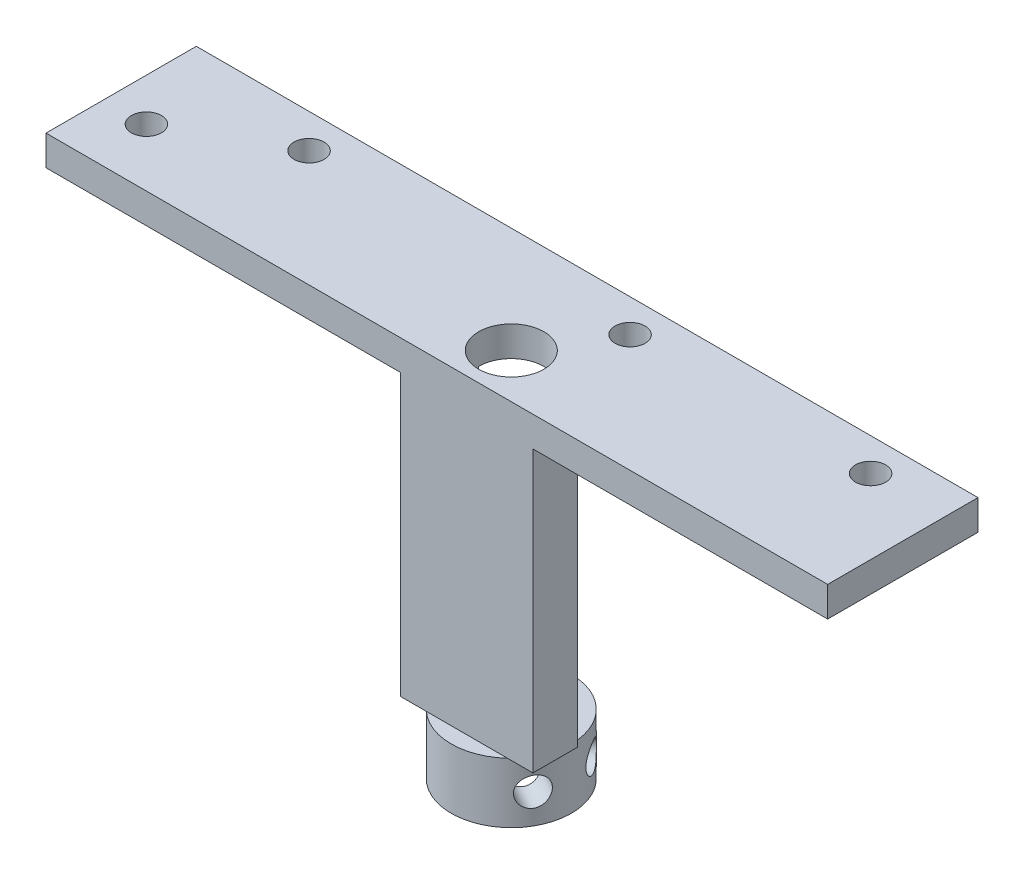
SolidWorks part; units mm, degrees
ref_plane "前视基准面" through (0, 0, 0) normal (0, 0, 1) x (1, 0, 0)
ref_plane "上视基准面" through (0, 0, 0) normal (0, 1, 0) x (1, 0, 0)
ref_plane "右视基准面" through (0, 0, 0) normal (1, 0, 0) x (0, 0, -1)
other "Configuration Table"
sketch "草图1" plane through (0, 0, 0) normal (0, 1, 0) x (1, 0, 0)
  line L1 (-39, -7.5) -> (39, -7.5)
  line L2 (-39, -7.5) -> (-39, 7.5)
  line L3 (-39, 7.5) -> (39, 7.5)
  line L4 (39, -7.5) -> (39, 7.5)
  line L5 (-39, -7.5) -> (39, 7.5) construction
  line L6 (-39, 7.5) -> (39, -7.5) construction
  point P0 (0, 0)
  dimension "D1" = 15
  dimension "D2" = 78
extrude "凸台-拉伸1" add sketch "草图1" along normal blind 3 contours L2 L1 L4 L3
sketch "草图3" plane through (0, 3, 0) normal (0, 1, 0) x (1, 0, 0)
  line L0 (-39, -7.5) -> (-39, 7.5) construction
  line L1 (-39, 7.5) -> (39, 7.5) construction
  circle A0 centre (-34.76, -1.72) radius 1.5
  circle A1 centre (-24.35, 4.1) radius 1.5
  circle A2 centre (31.56, 4.2217) radius 1.5
  circle A3 centre (7.56, 4.2217) radius 1.5
  dimension "D1" = 4.24
  dimension "D2" = 10.41
  dimension "D3" = 3.4
  dimension "D4" = 5.82
  dimension "D5" = 31.91
  dimension "D6" = 24
extrude "切除-拉伸1" cut sketch "草图3" against normal blind 3
sketch "草图4" plane through (0, 3, 0) normal (0, 1, 0) x (1, 0, 0)
  line L0 (-39, -7.5) -> (-39, 7.5) construction
  circle A0 centre (-3, -1.2342) radius 6
  dimension "D1" = 36
extrude "凸台-拉伸2" add sketch "草图4" along normal blind 18
sketch "草图5" plane through (0, 21, 0) normal (0, 1, 0) x (1, 0, 0)
  circle A0 centre (-3, -1.2342) radius 4.5
extrude "切除-拉伸2" cut sketch "草图5" against normal blind 21
hole_wizard "Ø2.0mm 暗销孔2" positions "3D草图5" profile "草图8" hole size "Ø2.0" standard "ANSI Metric"
sketch3d "3D草图5"
  point P0 (-7.9013, 17.3421, 4.6949)
  point P2 (1.0718, 17.1648, 5.6411)
sketch "草图8" plane through (-7.9013, 17.3421, 4.6949) normal (0, 1, 0) x (0.5768, 0, 0.8169)
  line L0 (0, 0) -> (0, 6)
  line L1 (0, 6) -> (1.5, 4.5)
  line L2 (1.5, 4.5) -> (1.5, 0)
  line L5 (1.5, 0) -> (0, 0)
  line L10 (0, 6) -> (-1.5, 4.5) construction
  line L11 (0, -6.35) -> (0, 107.95) construction
  dimension "孔直径" = 3
  dimension "孔深度" = 6
  dimension "导头角度" = 90
sketch "草图10" plane through (0, 0, -7.5) normal (0, 0, -1) x (-1, 0, 0)
  line L0 (39, 3) -> (-39, 3) construction
  line L1 (0, 3) -> (6, 3)
  line L2 (0, 3) -> (0, 13)
  line L3 (0, 13) -> (6, 13)
  line L4 (6, 3) -> (6, 13)
  dimension "D1" = 6
  dimension "D2" = 10
extrude "切除-拉伸3" cut sketch "草图10" against normal blind 7
sketch "草图13" plane through (0, 0, -7.5) normal (0, 0, -1) x (-1, 0, 0)
  line L0 (39, 3) -> (-39, 3) construction
  line L1 (-6.6034, 3) -> (13.2323, 3)
  line L2 (-6.6034, 3) -> (-6.6034, 24.6102)
  line L3 (-6.6034, 24.6102) -> (13.2323, 24.6102)
  line L4 (13.2323, 3) -> (13.2323, 24.6102)
extrude "切除-拉伸4" cut sketch "草图13" against normal blind 20
sketch "草图14" plane through (0, 3, 0) normal (0, 1, 0) x (1, 0, 0)
  line L1 (-8.751, 3.9817) -> (2.7721, 3.9817)
  line L2 (-8.751, 3.9817) -> (-8.751, -6.5086)
  line L3 (-8.751, -6.5086) -> (2.7721, -6.5086)
  line L4 (2.7721, 3.9817) -> (2.7721, -6.5086)
extrude "凸台-拉伸3" add sketch "草图14" against normal blind 3
sketch "草图18" plane through (0, 0, 0) normal (0, -1, 0) x (1, 0, 0)
  line L1 (-39, 7.5) -> (39, 7.5)
  line L2 (-39, 7.5) -> (-39, 15.5)
  line L3 (-39, 15.5) -> (39, 15.5)
  line L4 (39, 7.5) -> (39, 15.5)
  dimension "D1" = 8
extrude "凸台-拉伸4" add sketch "草图18" against normal blind 3
sketch "草图19" plane through (0, 0, 0) normal (0, -1, 0) x (1, 0, 0)
  line L0 (39, 15.5) -> (-39, 15.5) construction
  line L1 (-17.5447, 15.5) -> (19.2232, 15.5)
  line L2 (-17.5447, 15.5) -> (-17.5447, 13)
  line L3 (-17.5447, 13) -> (19.2232, 13)
  line L4 (19.2232, 15.5) -> (19.2232, 13)
  dimension "D1" = 2.5
extrude "凸台-拉伸5" add sketch "草图19" along normal blind 12.5
sketch "草图20" plane through (0, 0, 13) normal (0, 0, -1) x (-1, 0, 0)
  circle A0 centre (-6.7687, -6.2144) radius 1.65
  circle A1 centre (6.2313, -6.2144) radius 1.65
  dimension "D1" = 13
sketch "草图23" plane through (0, 0, 13) normal (0, 0, -1) x (-1, 0, 0)
  line L0 (-19.2232, -12.5) -> (-19.2232, 0) construction
  circle A4 centre (-8.6032, -6.0559) radius 1.65
  circle A5 centre (2.5968, -6.0559) radius 1.65
  dimension "D1" = 10.62
  dimension "D2" = 11.2
extrude "切除-拉伸6" cut sketch "草图23" against normal blind 12.5
sketch "草图24" plane through (0, 0, 13) normal (0, 0, -1) x (-1, 0, 0)
  circle A0 centre (-8.6032, -6.0559) radius 1.65 construction
  circle A1 centre (-8.6032, -6.0559) radius 1.65
  circle A2 centre (2.5968, -6.0559) radius 1.65 construction
  circle A3 centre (2.5968, -6.0559) radius 1.65
  circle A4 centre (4.1968, -6.0559) radius 1.6
  dimension "D2" = 12.8
  dimension "D1" = 11.2
sketch "草图25" plane through (0, 0, 13) normal (0, 0, -1) x (-1, 0, 0)
  line L1 (0.2124, -3.7444) -> (4.449, -3.7444)
  line L2 (0.2124, -3.7444) -> (0.2124, -9.1085)
  line L3 (0.2124, -9.1085) -> (4.449, -9.1085)
  line L4 (4.449, -3.7444) -> (4.449, -9.1085)
extrude "凸台-拉伸7" add sketch "草图25" against normal blind 2.5
sketch "草图26" plane through (0, 0, 13) normal (0, 0, -1) x (-1, 0, 0)
  circle A0 centre (4.1968, -6.0559) radius 1.6 construction
  circle A1 centre (4.1968, -6.0559) radius 1.6
extrude "切除-拉伸7" cut sketch "草图26" against normal blind 2.5
sketch "草图27" plane through (0, 0, 13) normal (0, 0, -1) x (-1, 0, 0)
  line L1 (-13.0523, -3.3946) -> (8.2937, -3.3946)
  line L2 (-13.0523, -3.3946) -> (-13.0523, -9.9889)
  line L3 (-13.0523, -9.9889) -> (8.2937, -9.9889)
  line L4 (8.2937, -3.3946) -> (8.2937, -9.9889)
extrude "凸台-拉伸8" add sketch "草图27" against normal blind 2.5
sketch "草图28" plane through (0, 0, 13) normal (0, 0, -1) x (-1, 0, 0)
  line L1 (-19.2232, -12.5) -> (17.544, -12.5)
  line L2 (-19.2232, -12.5) -> (-19.2232, -18.4182)
  line L3 (-19.2232, -18.4182) -> (17.544, -18.4182)
  line L4 (17.544, -12.5) -> (17.544, -18.4182)
extrude "凸台-拉伸9" add sketch "草图28" against normal blind 2.5
sketch "草图29" plane through (0, 0, 13) normal (0, 0, -1) x (-1, 0, 0)
  line L1 (-14.4639, -11.6442) -> (13.1964, -11.6442)
  line L2 (-14.4639, -11.6442) -> (-14.4639, -15.1442)
  line L3 (-14.4639, -15.1442) -> (13.1964, -15.1442)
  line L4 (13.1964, -11.6442) -> (13.1964, -15.1442)
  dimension "D1" = 3.5
extrude "切除-拉伸9" cut sketch "草图29" against normal blind 2.5
sketch "草图30" plane through (0, 3, 0) normal (0, 1, 0) x (1, 0, 0)
  line L0 (39, -15.5) -> (39, 7.5) construction
  line L1 (-39, -15.5) -> (39, -15.5)
  line L2 (-39, -15.5) -> (-39, -7.5)
  line L3 (-39, -7.5) -> (39, -7.5)
  line L4 (39, -15.5) -> (39, -7.5)
  line L5 (-39, 7.5) -> (39, 7.5) construction
  dimension "D1" = 15
extrude "切除-拉伸10" cut sketch "草图30" against normal blind 100
sketch "草图31" plane through (0, 0, 0) normal (0, -1, 0) x (1, 0, 0)
  line L0 (39, 7.5) -> (-39, 7.5) construction
  line L1 (-29.754, 7.5) -> (31.0662, 7.5)
  line L2 (-29.754, 7.5) -> (-29.754, 4.5)
  line L3 (-29.754, 4.5) -> (31.0662, 4.5)
  line L4 (31.0662, 7.5) -> (31.0662, 4.5)
  dimension "D1" = 3
extrude "凸台-拉伸10" add sketch "草图31" along normal blind 49
sketch "草图32" plane through (0, 0, 4.5) normal (0, 0, -1) x (-1, 0, 0)
  line L0 (-24.1534, -35.8541) -> (23.8466, -35.8541)
  line L1 (-24.1893, -43.0541) -> (23.8107, -43.0541)
  line L2 (-24.1893, -43.0541) -> (-24.1893, -46.2541)
  line L3 (-24.1893, -46.2541) -> (23.8107, -46.2541)
  line L4 (23.8107, -43.0541) -> (23.8107, -46.2541)
  line L5 (-24.1534, -35.8541) -> (-24.1534, -39.0541)
  line L6 (-24.1534, -39.0541) -> (23.8466, -39.0541)
  line L7 (23.8466, -35.8541) -> (23.8466, -39.0541)
  line L8 (-24.1733, -28.6541) -> (23.8267, -28.6541)
  line L9 (-24.1733, -28.6541) -> (-24.1733, -31.8541)
  line L10 (-24.1733, -31.8541) -> (23.8267, -31.8541)
  line L11 (23.8267, -28.6541) -> (23.8267, -31.8541)
  line L12 (-24.2052, -21.4541) -> (23.7948, -21.4541)
  line L13 (-24.2052, -21.4541) -> (-24.2052, -24.6541)
  line L14 (-24.2052, -24.6541) -> (23.7948, -24.6541)
  line L15 (23.7948, -21.4541) -> (23.7948, -24.6541)
  line L16 (-24.1756, -14.2541) -> (23.8244, -14.2541)
  line L17 (-24.1756, -14.2541) -> (-24.1756, -17.4541)
  line L18 (-24.1756, -17.4541) -> (23.8244, -17.4541)
  line L19 (23.8244, -14.2541) -> (23.8244, -17.4541)
  line L20 (-24.2763, -8.0541) -> (23.7237, -8.0541)
  line L21 (-24.2763, -8.0541) -> (-24.2763, -11.2541)
  line L22 (-24.2763, -11.2541) -> (23.7237, -11.2541)
  line L23 (23.7237, -8.0541) -> (23.7237, -11.2541)
  dimension "D1" = 3.2
  dimension "D2" = 48
  dimension "D3" = 4
  dimension "D4" = 4
  dimension "D5" = 4
  dimension "D6" = 4
  dimension "D7" = 3
extrude "切除-拉伸11" cut sketch "草图32" against normal blind 49 contours L19 L16 L17 L18 | L15 L12 L13 L14 | L11 L8 L9 L10 | L7 L0 L5 L6 | L4 L1 L2 L3 | L20 L23 L22 L21
sketch "草图33" plane through (31.0662, 0, 0) normal (1, 0, 0) x (0, 0, -1)
  line L3 (-7.5, 0) -> (7.5, 0)
  line L4 (-7.5, 0) -> (-7.5, -49.0597)
  line L5 (-7.5, -49.0597) -> (7.5, -49.0597)
  line L6 (7.5, 0) -> (7.5, -49.0597)
extrude "切除-拉伸12" cut sketch "草图33" against normal blind 100
sketch "草图34" plane through (0, 0, 0) normal (0, -1, 0) x (1, 0, 0)
  line L0 (39, 7.5) -> (39, -7.5) construction
  circle A0 centre (3, 3.0716) radius 4.25
  dimension "D1" = 36
extrude "凸台-拉伸11" add sketch "草图34" along normal blind 49
sketch "草图35" plane through (0, -49, 0) normal (0, -1, 0) x (1, 0, 0)
  circle A0 centre (3, 3.0716) radius 6
extrude "凸台-拉伸12" add sketch "草图35" against normal blind 6
sketch "草图36" plane through (0, 0, -7.5) normal (0, 0, -1) x (-1, 0, 0)
  line L0 (1.25, -43) -> (1.25, 0) construction
  line L1 (-7.25, 0) -> (1.25, 0)
  line L2 (-7.25, 0) -> (-7.25, -40)
  line L3 (-7.25, -40) -> (1.25, -40)
  line L4 (1.25, 0) -> (1.25, -40)
  dimension "D1" = 40
extrude "切除-拉伸13" cut sketch "草图36" against normal blind 11
sketch "草图37" plane through (0, -49, 0) normal (0, -1, 0) x (1, 0, 0)
  circle A0 centre (3, 3.0716) radius 3.25
extrude "切除-拉伸16" cut sketch "草图37" against normal blind 100
sketch "草图39" plane through (0, 0, 3.5) normal (0, 0, -1) x (-1, 0, 0)
  line L0 (1.2283, -40) -> (1.2283, 0) construction
  line L1 (-7.2283, -40) -> (1.2283, -40)
  line L2 (-7.2283, -40) -> (-7.2283, -24)
  line L3 (-7.2283, -24) -> (1.2283, -24)
  line L4 (1.2283, -40) -> (1.2283, -24)
  dimension "D1" = 16
extrude "切除-拉伸17" cut sketch "草图39" against normal blind 1.25
hole_wizard "Ø3.0mm 暗销孔1" positions "3D草图7" profile "草图41" hole size "Ø3.0" standard "ANSI Metric"
sketch3d "3D草图7"
  point P0 (3.0692, -45.9266, -2.928)
sketch "草图41" plane through (3.0692, -45.9266, -2.928) normal (0, 1, 0) x (-0.9999, 0, -0.0115)
  line L0 (0, 0) -> (0, 5)
  line L1 (0, 5) -> (1.425, 4.1438)
  line L2 (1.425, 4.1438) -> (1.425, 0)
  line L5 (1.425, 0) -> (0, 0)
  line L10 (0, 5) -> (-1.425, 4.1438) construction
  line L11 (0, -6.35) -> (0, 107.95) construction
  dimension "孔直径" = 2.85
  dimension "孔深度" = 5
  dimension "导头角度" = 118
ref_plane "基准面1" through (0, -46, 0) normal (0, -1, 0) x (-1, 0, 0)
sketch "草图42" plane through (0, -46, 0) normal (0, -1, 0) x (-1, 0, 0)
  line L0 (-3, -3.0716) -> (-3, 2.9284)
  line L1 (-3, -3.0716) -> (2.1962, -6.0716)
  line L2 (-3, -3.0716) -> (-8.1962, -6.0716)
  circle A0 centre (-3, -3.0716) radius 6 construction
  dimension "D1" = 120
  dimension "D2" = 120
hole_wizard "Ø3.0mm 暗销孔2" positions "3D草图8" profile "草图44" hole size "Ø3.0" standard "ANSI Metric"
sketch3d "3D草图8"
  point P0 (-2.1944, -45.9809, 6.0747)
sketch "草图44" plane through (-2.1944, -45.9809, 6.0747) normal (0, 1, 0) x (0.5005, 0, 0.8657)
  line L0 (0, 0) -> (0, 5)
  line L1 (0, 5) -> (1.425, 4.1438)
  line L2 (1.425, 4.1438) -> (1.425, 0)
  line L5 (1.425, 0) -> (0, 0)
  line L10 (0, 5) -> (-1.425, 4.1438) construction
  line L11 (0, -6.35) -> (0, 107.95) construction
  dimension "孔直径" = 2.85
  dimension "孔深度" = 5
  dimension "导头角度" = 118
hole_wizard "Ø3.0mm 暗销孔3" positions "3D草图9" profile "草图45" hole size "Ø3.0" standard "ANSI Metric"
sketch3d "3D草图9"
  point P0 (8.2058, -46.04, 6.0548)
sketch "草图45" plane through (8.2058, -46.04, 6.0548) normal (0, 1, 0) x (0.4972, 0, -0.8676)
  line L0 (0, 0) -> (0, 5)
  line L1 (0, 5) -> (1.425, 4.1438)
  line L2 (1.425, 4.1438) -> (1.425, 0)
  line L5 (1.425, 0) -> (0, 0)
  line L10 (0, 5) -> (-1.425, 4.1438) construction
  line L11 (0, -6.35) -> (0, 107.95) construction
  dimension "孔直径" = 2.85
  dimension "孔深度" = 5
  dimension "导头角度" = 118
sketch "草图46" plane through (0, 3, 0) normal (0, 1, 0) x (1, 0, 0)
  line L0 (39, -7.5) -> (-39, -7.5) construction
  line L1 (-3.6375, -7.5) -> (9.5896, -7.5)
  line L2 (-3.6375, -7.5) -> (-3.6375, -3.0716)
  line L3 (-3.6375, -3.0716) -> (9.5896, -3.0716)
  line L4 (9.5896, -7.5) -> (9.5896, -3.0716)
extrude "凸台-拉伸13" add sketch "草图46" against normal blind 46
sketch "草图48" plane through (0, -49, 0) normal (0, -1, 0) x (1, 0, 0)
  line L1 (-0.25, 3.0716) -> (6.25, 3.0716)
  line L2 (-0.25, 3.0716) -> (6.25, 3.0716)
  arc A1 (6.25, 3.0716) -> (-0.25, 3.0716) centre (3, 3.0716) ccw
  arc A2 (6.25, 3.0716) -> (-0.25, 3.0716) centre (3, 3.0716) ccw
  dimension "D1" = 0
extrude "切除-拉伸18" cut sketch "草图48" against normal blind 55
sketch "草图49" plane through (0, 0, 0) normal (0, -1, 0) x (1, 0, 0)
  line L9 (-0.25, 3.0716) -> (-3.6375, 3.0716)
  line L10 (-3.6375, 3.0716) -> (-3.6375, 7.5)
  line L11 (-3.6375, 7.5) -> (-39, 7.5)
  line L12 (-39, 7.5) -> (-39, -7.5)
  line L13 (-39, -7.5) -> (39, -7.5)
  line L14 (39, -7.5) -> (39, 7.5)
  line L15 (39, 7.5) -> (9.5896, 7.5)
  line L16 (9.5896, 7.5) -> (9.5896, 3.0716)
  line L17 (9.5896, 3.0716) -> (6.25, 3.0716)
  line L18 (-0.25, 3.0716) -> (-3.6375, 3.0716)
  line L19 (-3.6375, 3.0716) -> (-3.6375, 7.5)
  line L20 (-3.6375, 7.5) -> (-39, 7.5)
  line L21 (-39, 7.5) -> (-39, -7.5)
  line L22 (-39, -7.5) -> (39, -7.5)
  line L23 (39, -7.5) -> (39, 7.5)
  line L24 (39, 7.5) -> (9.5896, 7.5)
  line L25 (9.5896, 7.5) -> (9.5896, 3.0716)
  line L26 (9.5896, 3.0716) -> (6.25, 3.0716)
  arc A1 (-0.25, 3.0716) -> (6.25, 3.0716) centre (3, 3.0716) ccw
  arc A2 (-0.25, 3.0716) -> (6.25, 3.0716) centre (3, 3.0716) ccw
  dimension "D1" = 0
extrude "凸台-拉伸14" add sketch "草图49" along normal blind 15
sketch "草图50" plane through (0, 0, 0) normal (0, 1, 0) x (1, 0, 0)
  circle A1 centre (-34.76, -1.72) radius 1.5
  circle A2 centre (-34.76, -1.72) radius 1.5
  dimension "D1" = 0
extrude "切除-拉伸19" cut sketch "草图50" against normal blind 15
sketch "草图51" plane through (0, 0, 0) normal (0, 1, 0) x (1, 0, 0)
  circle A1 centre (-24.35, 4.1) radius 1.5
  circle A2 centre (-24.35, 4.1) radius 1.5
  dimension "D1" = 0
extrude "切除-拉伸20" cut sketch "草图51" against normal blind 15
sketch "草图52" plane through (0, 0, 0) normal (0, 1, 0) x (1, 0, 0)
  circle A1 centre (7.56, 4.2217) radius 1.5
  circle A2 centre (7.56, 4.2217) radius 1.5
  dimension "D1" = 0
extrude "切除-拉伸21" cut sketch "草图52" against normal blind 15
sketch "草图53" plane through (0, 0, 0) normal (0, 1, 0) x (1, 0, 0)
  circle A1 centre (31.56, 4.2217) radius 1.5
  circle A2 centre (31.56, 4.2217) radius 1.5
  dimension "D1" = 0
extrude "切除-拉伸22" cut sketch "草图53" against normal blind 15
sketch "草图54" plane through (0, 3, 0) normal (0, 1, 0) x (1, 0, 0)
  line L4 (-39, 7.5) -> (-39, -7.5)
  line L5 (-39, -7.5) -> (39, -7.5)
  line L6 (39, -7.5) -> (39, 7.5)
  line L7 (39, 7.5) -> (-39, 7.5)
  line L8 (-39, 7.5) -> (-39, -7.5)
  line L9 (-39, -7.5) -> (39, -7.5)
  line L10 (39, -7.5) -> (39, 7.5)
  line L11 (39, 7.5) -> (-39, 7.5)
  dimension "D1" = 0
extrude "切除-拉伸23" cut sketch "草图54" against normal blind 15
ref_plane "基准面2" through (0, -46, 0) normal (0, -1, 0) x (-1, 0, 0)
sketch "草图55" plane through (0, -46, 0) normal (0, -1, 0) x (-1, 0, 0)
  line L0 (-3, -3.0716) -> (2.1962, -0.0716)
  line L1 (-3, -3.0716) -> (-8.1962, -0.0716)
  line L2 (-3, -3.0716) -> (-3, 2.9284) construction
  circle A0 centre (-3, -3.0716) radius 6 construction
  dimension "D1" = 60
  dimension "D2" = 60
hole_wizard "Ø3.0mm 暗销孔4" positions "3D草图10" profile "草图56" hole size "Ø3.0" standard "ANSI Metric"
sketch3d "3D草图10"
  point P0 (-2.2068, -45.9744, 0.0901)
sketch "草图56" plane through (-2.2068, -45.9744, 0.0901) normal (0, 1, 0) x (-0.4969, 0, 0.8678)
  line L0 (0, 0) -> (0, 5)
  line L1 (0, 5) -> (1.425, 4.1438)
  line L2 (1.425, 4.1438) -> (1.425, 0)
  line L5 (1.425, 0) -> (0, 0)
  line L10 (0, 5) -> (-1.425, 4.1438) construction
  line L11 (0, -6.35) -> (0, 107.95) construction
  dimension "孔直径" = 2.85
  dimension "孔深度" = 5
  dimension "导头角度" = 118
hole_wizard "Ø3.0mm 暗销孔5" positions "3D草图11" profile "草图57" hole size "Ø3.0" standard "ANSI Metric"
sketch3d "3D草图11"
  point P0 (8.192, -46.013, 0.0645)
sketch "草图57" plane through (8.192, -46.013, 0.0645) normal (0, 1, 0) x (-0.5012, 0, -0.8653)
  line L0 (0, 0) -> (0, 5)
  line L1 (0, 5) -> (1.425, 4.1438)
  line L2 (1.425, 4.1438) -> (1.425, 0)
  line L5 (1.425, 0) -> (0, 0)
  line L10 (0, 5) -> (-1.425, 4.1438) construction
  line L11 (0, -6.35) -> (0, 107.95) construction
  dimension "孔直径" = 2.85
  dimension "孔深度" = 5
  dimension "导头角度" = 118
